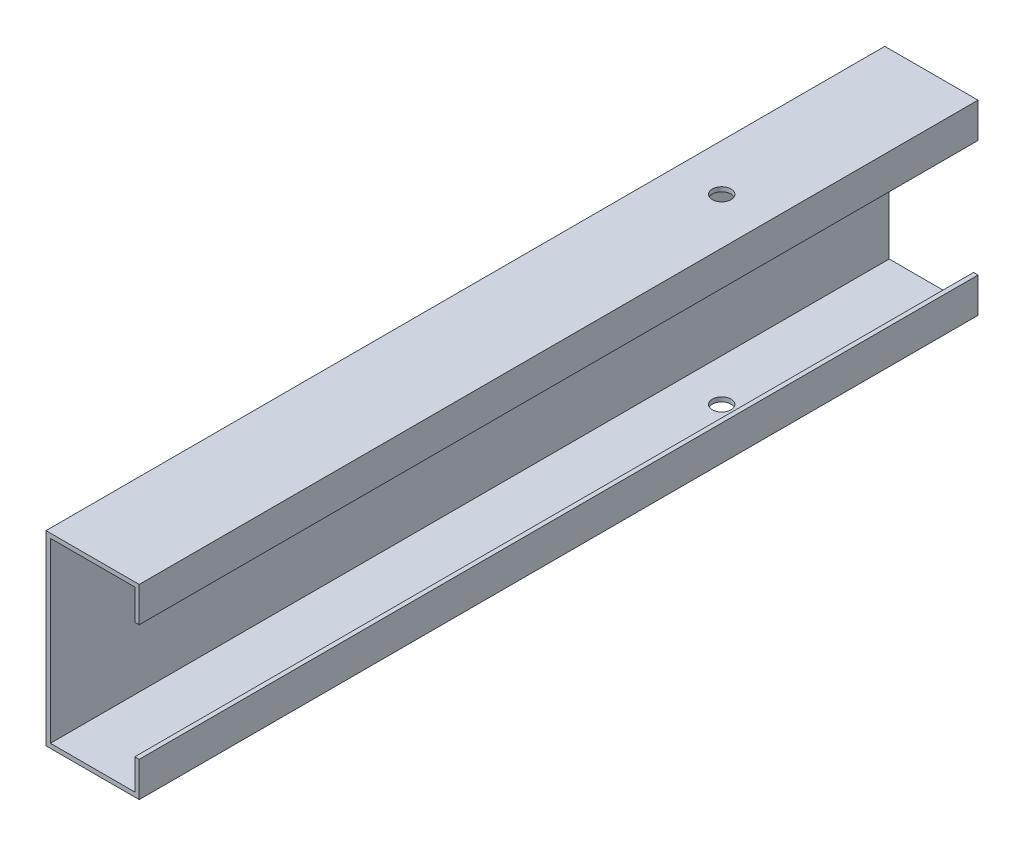
SolidWorks part; units mm, degrees
ref_plane "Front Plane" through (0, 0, 0) normal (0, 0, 1) x (1, 0, 0)
ref_plane "Top Plane" through (0, 0, 0) normal (0, 1, 0) x (1, 0, 0)
ref_plane "Right Plane" through (0, 0, 0) normal (1, 0, 0) x (0, 0, -1)
sketch "Croquis1" plane through (0, 0, 0) normal (0, 0, 1) x (1, 0, 0)
  line L0 (20, 40) -> (-20, 40)
  line L1 (-20, -40) -> (20, -40) construction
  line L2 (-20, -40) -> (-20, 40) construction
  line L3 (-20, 40) -> (20, 40) construction
  line L4 (20, -40) -> (20, 40) construction
  line L5 (-20, -40) -> (20, 40) construction
  line L6 (-20, 40) -> (20, -40) construction
  line L7 (-20, 40) -> (-20, -40)
  line L8 (-20, -40) -> (20, -40)
  line L9 (20, -40) -> (20, -38.1)
  line L10 (20, -25) -> (20, -38.1)
  line L11 (-18.1, -38.1) -> (-18.1, 38.1)
  line L12 (-18.1, 38.1) -> (18.1, 38.1)
  line L13 (55, 0) -> (-55, 0) construction
  line L14 (20, 40) -> (18.1, 40)
  line L15 (20, 40) -> (20, 25)
  line L16 (20, 25) -> (18.1, 25)
  line L17 (18.1, 38.1) -> (18.1, 25)
  line L18 (20, -25) -> (18.1, -25)
  line L19 (18.1, -38.1) -> (18.1, -25)
  line L20 (20, -40) -> (18.1, -40)
  line L21 (20, -40) -> (20, -25)
  line L22 (18.1, -38.1) -> (-18.1, -38.1)
  line L23 (20, 40) -> (20, 25)
  point P0 (0, 0)
  dimension "D1" = 40
  dimension "D2" = 80
  dimension "D3" = 1.9
  dimension "D5" = 1.9
  dimension "D6" = 1.9
  dimension "D7" = 15
extrude "Saliente-Extruir1" add sketch "Croquis1" along normal blind 360 contours L19 L22 L11 L12 L17 L16 L15 L0 L7 L8 L9 L10 L18
sketch "Croquis2" plane through (-20, 0, 0) normal (-1, 0, 0) x (0, 0, 1)
  line L0 (0, 0) -> (360, 0) construction
  line L1 (0, 40) -> (0, -40) construction
  line L2 (360, 40) -> (360, -40) construction
  line L3 (180, 40) -> (180, -40) construction
  line L4 (360, 40) -> (0, 40) construction
  line L5 (360, -40) -> (0, -40) construction
  circle A0 centre (270, 0) radius 4
  circle A1 centre (90, 0) radius 4
  dimension "D1" = 8
  dimension "D2" = 90
extrude "Cortar-Extruir1" cut sketch "Croquis2" against normal through all
sketch "Croquis3" plane through (0, 40, 0) normal (0, 1, 0) x (1, 0, 0)
  line L0 (0, 0) -> (0, -360) construction
  line L1 (20, -360) -> (-20, -360) construction
  line L2 (20, 0) -> (-20, 0) construction
  circle A0 centre (0, -90) radius 4
  point P11 (0, 0)
  dimension "D1" = 8
  dimension "D2" = 90
extrude "Cortar-Extruir2" cut sketch "Croquis3" against normal through all
